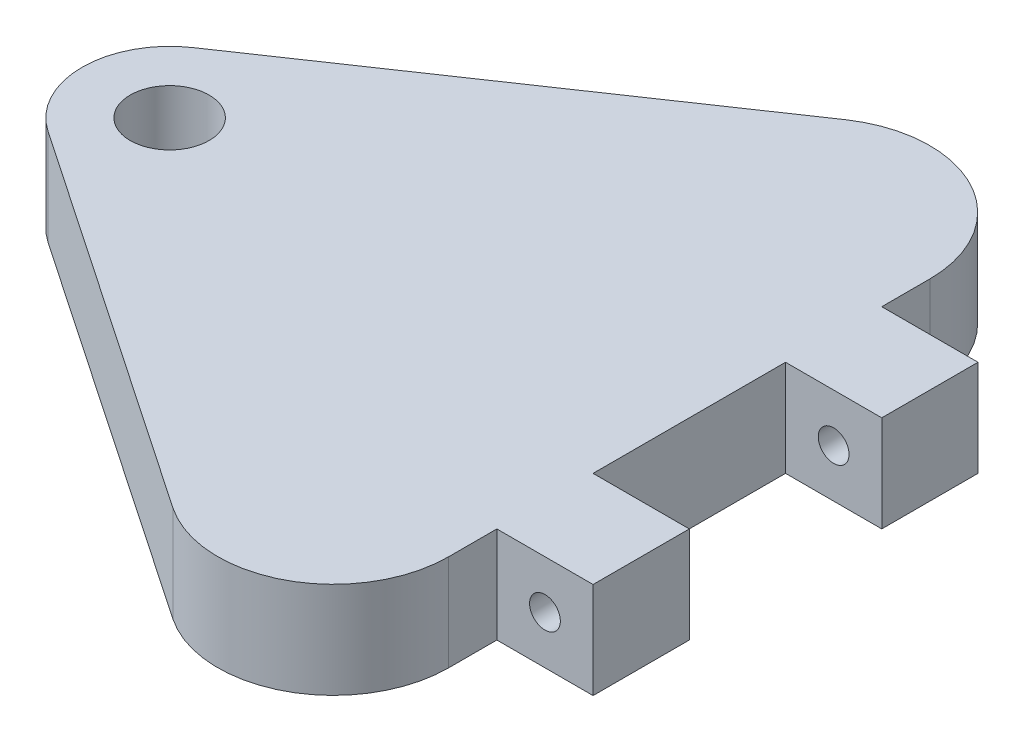
SolidWorks part; units mm, degrees
ref_plane "正面" through (0, 0, 0) normal (0, 0, 1) x (1, 0, 0)
ref_plane "平面" through (0, 0, 0) normal (0, 1, 0) x (1, 0, 0)
ref_plane "右側面" through (0, 0, 0) normal (1, 0, 0) x (0, 0, -1)
sketch "ｽｹｯﾁ1" plane through (0, 0, 0) normal (0, 1, 0) x (1, 0, 0)
  line L0 (-47.1103, 7.5296) -> (-6.7388, 34.9292)
  line L1 (12, 25) -> (12, -25)
  line L2 (-6.7388, -34.9292) -> (-47.1103, -7.5296)
  circle A2 centre (-42, 0) radius 4.1
  arc A3 (12, 25) -> (-6.7388, 34.9292) centre (0, 25) ccw
  arc A4 (-6.7388, -34.9292) -> (12, -25) centre (0, -25) ccw
  arc A5 (-47.1103, 7.5296) -> (-47.1103, -7.5296) centre (-42, 0) ccw
  dimension "D1" = 8.2
  dimension "D2" = 12
  dimension "D5" = 42
  dimension "D6" = 25
  dimension "D8" = 5
  dimension "D4" = 12
  dimension "D3" = 25
extrude "ﾎﾞｽ - 押し出し1" add sketch "ｽｹｯﾁ1" along normal blind 10
sketch "ｽｹｯﾁ2" plane through (0, 0, 0) normal (0, -1, 0) x (1, 0, 0)
  line L1 (-5.1, 19.9) -> (5.1, 19.9)
  line L2 (-5.1, 19.9) -> (-5.1, 30.1)
  line L3 (-5.1, 30.1) -> (5.1, 30.1)
  line L4 (5.1, 19.9) -> (5.1, 30.1)
  line L5 (-5.1, 19.9) -> (5.1, 30.1) construction
  line L6 (-5.1, 30.1) -> (5.1, 19.9) construction
  line L7 (-5.1, -19.9) -> (5.1, -19.9)
  line L8 (-5.1, -19.9) -> (-5.1, -30.1)
  line L9 (-5.1, -30.1) -> (5.1, -30.1)
  line L10 (5.1, -19.9) -> (5.1, -30.1)
  line L11 (-5.1, -19.9) -> (5.1, -30.1) construction
  line L12 (-5.1, -30.1) -> (5.1, -19.9) construction
  line L13 (-25.1, -5.1) -> (-14.9, -5.1)
  line L14 (-25.1, -5.1) -> (-25.1, 5.1)
  line L15 (-25.1, 5.1) -> (-14.9, 5.1)
  line L16 (-14.9, -5.1) -> (-14.9, 5.1)
  line L17 (-25.1, -5.1) -> (-14.9, 5.1) construction
  line L18 (-25.1, 5.1) -> (-14.9, -5.1) construction
  point P0 (0, 25)
  point P5 (0, -25)
  point P10 (-20, 0)
  point P16 (0, 0)
  dimension "D1" = 10.2
  dimension "D2" = 25
  dimension "D3" = 25
  dimension "D4" = 20
extrude "ｶｯﾄ - 押し出し1" cut sketch "ｽｹｯﾁ2" against normal blind 5
sketch "ｽｹｯﾁ3" plane through (12, 0, 0) normal (1, 0, 0) x (0, 0, -1)
  line L0 (-25, 10) -> (25, 10) construction
  line L1 (-20, 10) -> (-10, 10)
  line L2 (-20, 10) -> (-20, 0)
  line L3 (-20, 0) -> (-10, 0)
  line L4 (-10, 10) -> (-10, 0)
  line L5 (-20, 10) -> (-10, 0) construction
  line L6 (-20, 0) -> (-10, 10) construction
  line L7 (-25, 0) -> (25, 0) construction
  line L9 (10, 10) -> (20, 10)
  line L10 (10, 10) -> (10, 0)
  line L11 (10, 0) -> (20, 0)
  line L12 (20, 10) -> (20, 0)
  line L13 (10, 10) -> (20, 0) construction
  line L14 (10, 0) -> (20, 10) construction
  point P4 (-15, 5)
  point P13 (15, 5)
  dimension "D1" = 15
  dimension "D2" = 15
extrude "ﾎﾞｽ - 押し出し2" add sketch "ｽｹｯﾁ3" along normal blind 10
sketch "ｽｹｯﾁ4" plane through (0, 0, 0) normal (0, 0, 1) x (1, 0, 0)
  line L0 (22, 10) -> (22, 0) construction
  line L1 (22, 10) -> (12, 10) construction
  circle A0 centre (17, 5) radius 1.6
  point P4 (22, 5)
  point P7 (17, 10)
  dimension "D1" = 3.2
extrude "ｶｯﾄ - 押し出し2" cut sketch "ｽｹｯﾁ4" against normal through all both and the other way through all
